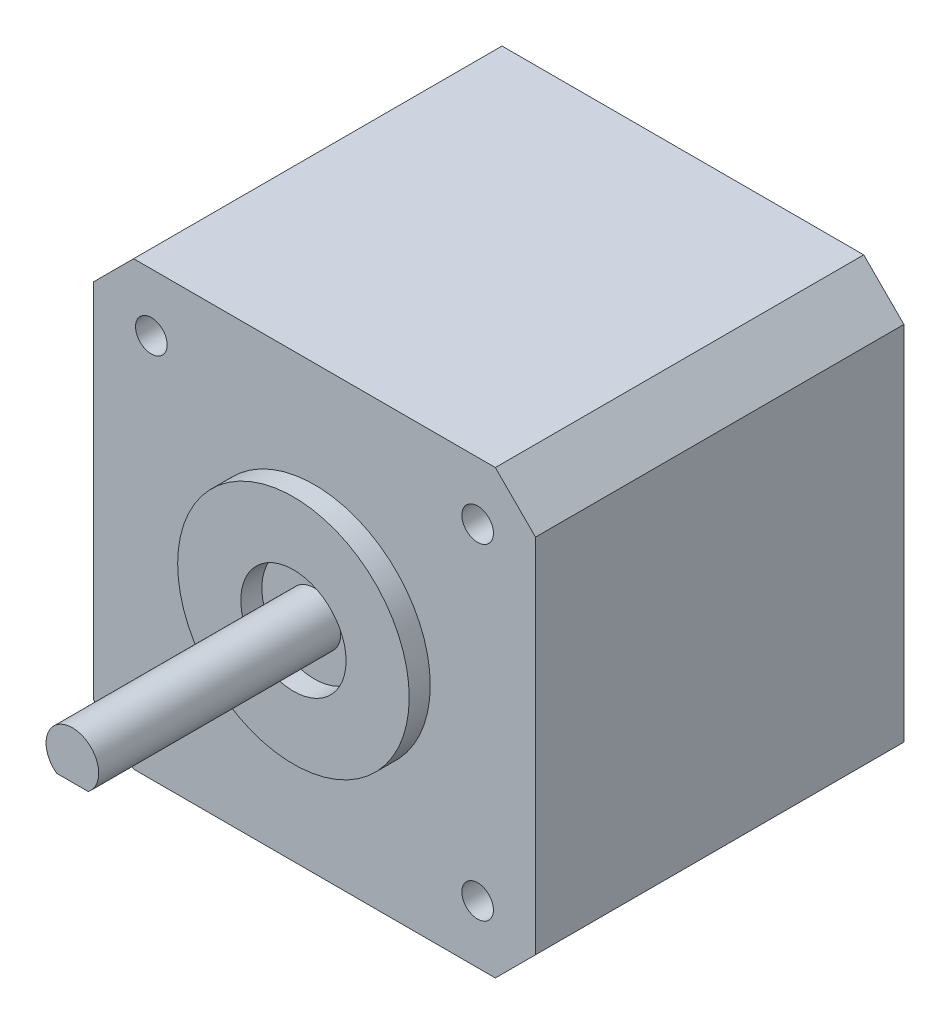
SolidWorks part; units mm, degrees
ref_plane "前视基准面" through (0, 0, 0) normal (0, 0, 1) x (1, 0, 0)
ref_plane "上视基准面" through (0, 0, 0) normal (0, 1, 0) x (1, 0, 0)
ref_plane "右视基准面" through (0, 0, 0) normal (1, 0, 0) x (0, 0, -1)
sketch "草图1" plane through (0, 0, 0) normal (0, 0, 1) x (1, 0, 0)
  line L5 (-17.1838, 21) -> (17.1838, 21)
  line L7 (-21, 17.1838) -> (-17.1838, 21)
  line L9 (21, 17.1838) -> (17.1838, 21)
  line L10 (-17.1838, -21) -> (-21, -17.1838)
  line L11 (-21, 17.1838) -> (-21, -17.1838)
  line L12 (17.1838, -21) -> (-17.1838, -21)
  line L13 (17.1838, -21) -> (21, -17.1838)
  line L14 (21, -17.1838) -> (21, 17.1838)
  point P0 (0, 0)
extrude "凸台-拉伸1" add sketch "草图1" along normal blind 35
sketch "草图2" plane through (0, 0, 35) normal (0, 0, 1) x (1, 0, 0)
  circle A0 centre (0, 0) radius 11
  circle A1 centre (0, 0) radius 5
extrude "凸台-拉伸2" add sketch "草图2" along normal blind 2
sketch "草图3" plane through (0, 0, 35) normal (0, 0, 1) x (1, 0, 0)
  circle A0 centre (0, 0) radius 2.5
extrude "凸台-拉伸3" add sketch "草图3" along normal blind 23
sketch "草图4" plane through (0, 0, 58) normal (0, 0, 1) x (1, 0, 0)
  line L2 (1.5, -2) -> (-1.5, -2)
  circle A1 centre (0, 0) radius 2.5
  arc A2 (-1.5, -2) -> (1.5, -2) centre (0, 0) ccw
  dimension "D1" = 0
extrude "切除-拉伸1" cut sketch "草图4" against normal blind 18
sketch "草图5" plane through (0, 0, 35) normal (0, 0, 1) x (1, 0, 0)
  circle A0 centre (-15.5, 15.5) radius 1.5
  circle A1 centre (15.5, 15.5) radius 1.5
  circle A2 centre (15.5, -15.5) radius 1.5
  circle A3 centre (-15.5, -15.5) radius 1.5
  point P0 (0, 0)
  point P7 (0, 0)
  point P10 (0, 0)
  point P13 (0, 0)
  point P16 (0, 0)
  dimension "D1" = 4
extrude "切除-拉伸2" cut sketch "草图5" against normal blind 5
